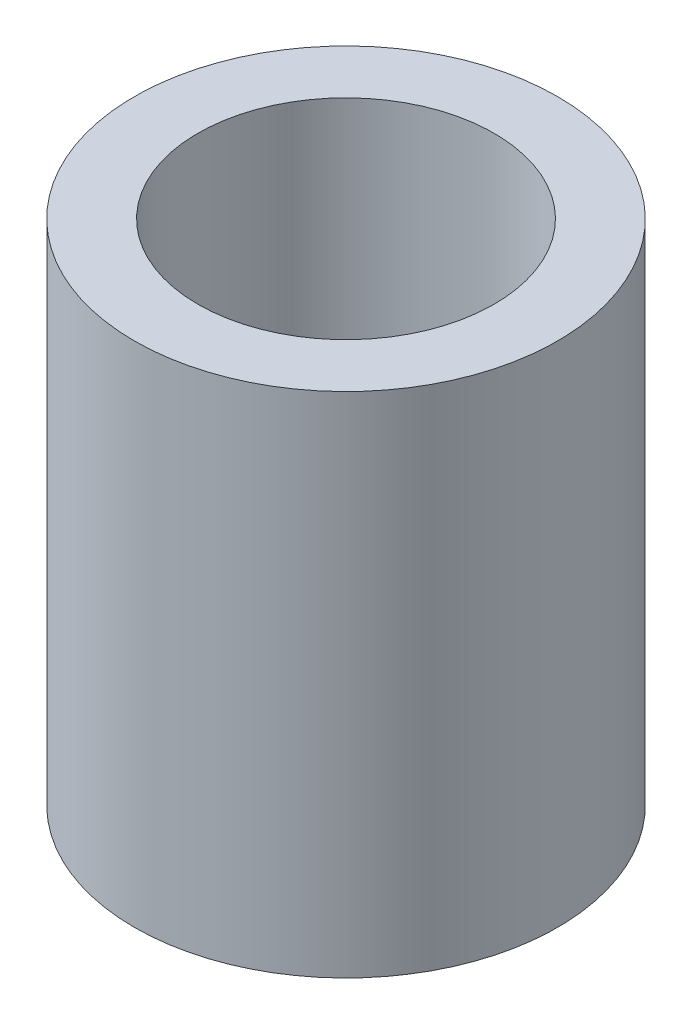
SolidWorks part; units mm, degrees
material "Custom Plastic"
ref_plane "X-Y Datum" through (0, 0, 0) normal (0, 0, 1) x (1, 0, 0)
ref_plane "X-Z Datum" through (0, 0, 0) normal (0, 1, 0) x (1, 0, 0)
ref_plane "Y-Z Datum" through (0, 0, 0) normal (1, 0, 0) x (0, 0, -1)
sketch "Sketch1" plane through (0, 0, 0) normal (0, 1, 0) x (1, 0, 0)
  circle A0 centre (0, 0) radius 2.8575
  circle A1 centre (0, 0) radius 2
  dimension "D1" = 4
  dimension "D2" = 5.715
extrude "Boss-Extrude1" add sketch "Sketch1" against normal blind 6.858
